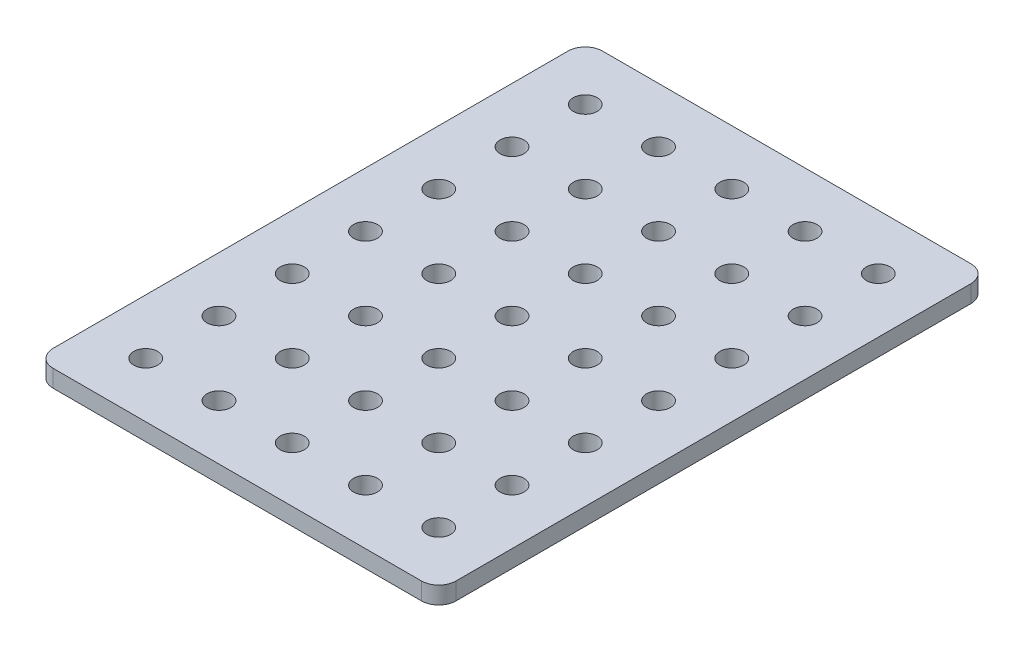
SolidWorks part; units mm, degrees
ref_plane "Front Plane" through (0, 0, 0) normal (0, 0, 1) x (1, 0, 0)
ref_plane "Top Plane" through (0, 0, 0) normal (0, 1, 0) x (1, 0, 0)
ref_plane "Right Plane" through (0, 0, 0) normal (1, 0, 0) x (0, 0, -1)
sketch "Sketch1" plane through (0, 0, 0) normal (0, 1, 0) x (1, 0, 0)
  line L0 (0, 47.625) -> (0, -47.625) construction
  line L1 (-34.925, 47.625) -> (34.925, 47.625)
  line L2 (-34.925, 47.625) -> (-34.925, -47.625)
  line L3 (-34.925, -47.625) -> (34.925, -47.625)
  line L4 (34.925, 47.625) -> (34.925, -47.625)
  line L5 (-34.925, 47.625) -> (34.925, -47.625) construction
  line L6 (-34.925, -47.625) -> (34.925, 47.625) construction
  line L8 (-34.925, 0) -> (34.925, 0) construction
  circle A0 centre (0, 0) radius 2.075
  circle A1 centre (-25.4, 0) radius 2.075
  circle A2 centre (-12.7, 0) radius 2.075
  circle A3 centre (12.7, 0) radius 2.075
  circle A4 centre (25.4, 0) radius 2.075
  circle A5 centre (-25.4, 12.7) radius 2.075
  circle A6 centre (-12.7, 12.7) radius 2.075
  circle A7 centre (0, 12.7) radius 2.075
  circle A8 centre (12.7, 12.7) radius 2.075
  circle A9 centre (25.4, 12.7) radius 2.075
  circle A10 centre (-25.4, 25.4) radius 2.075
  circle A11 centre (-12.7, 25.4) radius 2.075
  circle A12 centre (0, 25.4) radius 2.075
  circle A13 centre (12.7, 25.4) radius 2.075
  circle A14 centre (25.4, 25.4) radius 2.075
  circle A15 centre (-25.4, 38.1) radius 2.075
  circle A16 centre (-12.7, 38.1) radius 2.075
  circle A17 centre (0, 38.1) radius 2.075
  circle A18 centre (12.7, 38.1) radius 2.075
  circle A19 centre (25.4, 38.1) radius 2.075
  circle A20 centre (-25.4, -12.7) radius 2.075
  circle A21 centre (-12.7, -12.7) radius 2.075
  circle A22 centre (0, -12.7) radius 2.075
  circle A23 centre (12.7, -12.7) radius 2.075
  circle A24 centre (25.4, -12.7) radius 2.075
  circle A25 centre (-25.4, -25.4) radius 2.075
  circle A26 centre (-12.7, -25.4) radius 2.075
  circle A27 centre (0, -25.4) radius 2.075
  circle A28 centre (12.7, -25.4) radius 2.075
  circle A29 centre (25.4, -25.4) radius 2.075
  circle A30 centre (-25.4, -38.1) radius 2.075
  circle A31 centre (-12.7, -38.1) radius 2.075
  circle A32 centre (0, -38.1) radius 2.075
  circle A33 centre (12.7, -38.1) radius 2.075
  circle A34 centre (25.4, -38.1) radius 2.075
  point P0 (0, 0)
  dimension "D7" = 4.15
  dimension "D1" = 69.85
  dimension "D2" = 95.25
  dimension "D3" = 25.4
  dimension "D4" = 12.7
  dimension "D5" = 25.4
  dimension "D6" = 12.7
  dimension "D9" = 12.7
  dimension "D11" = 12.7
  dimension "D8" = 4
  dimension "D10" = 4
extrude "Boss-Extrude1" add sketch "Sketch1" along normal mid plane 3
fillet "Fillet1" radius 3 4 edges at (-34.925, 0, 47.625) (-34.925, 0, -47.625) (34.925, 0, -47.625) (34.925, 0, 47.625)
